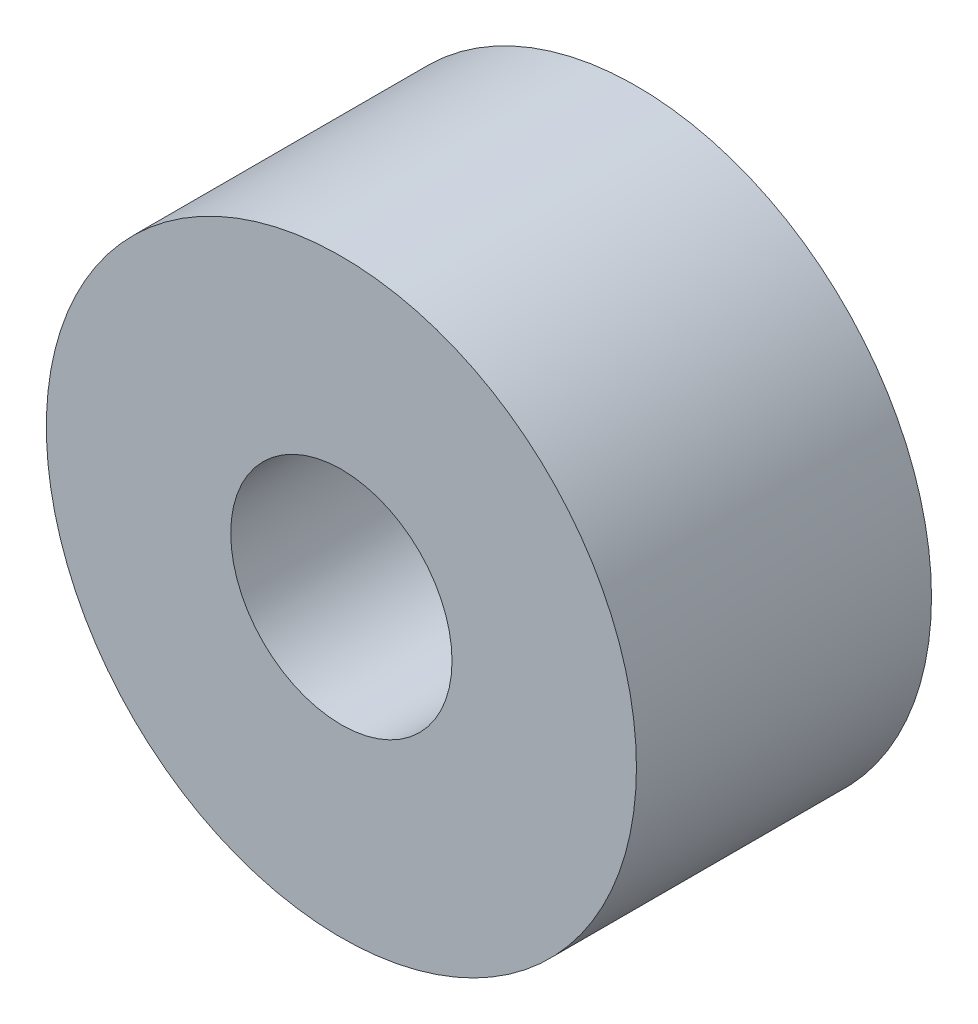
SolidWorks part; units mm, degrees
ref_plane "Front Plane" through (0, 0, 0) normal (0, 0, 1) x (1, 0, 0)
ref_plane "Top Plane" through (0, 0, 0) normal (0, 1, 0) x (1, 0, 0)
ref_plane "Right Plane" through (0, 0, 0) normal (1, 0, 0) x (0, 0, -1)
sketch "Sketch2" plane through (0, 0, 0) normal (0, 0, 1) x (1, 0, 0)
  circle A0 centre (0, 0) radius 6.35
  circle A1 centre (0, 0) radius 2.3813
  dimension "D1" = 12.7
  dimension "D2" = 4.7625
extrude "Boss-Extrude1" add sketch "Sketch2" along normal mid plane 6.35
